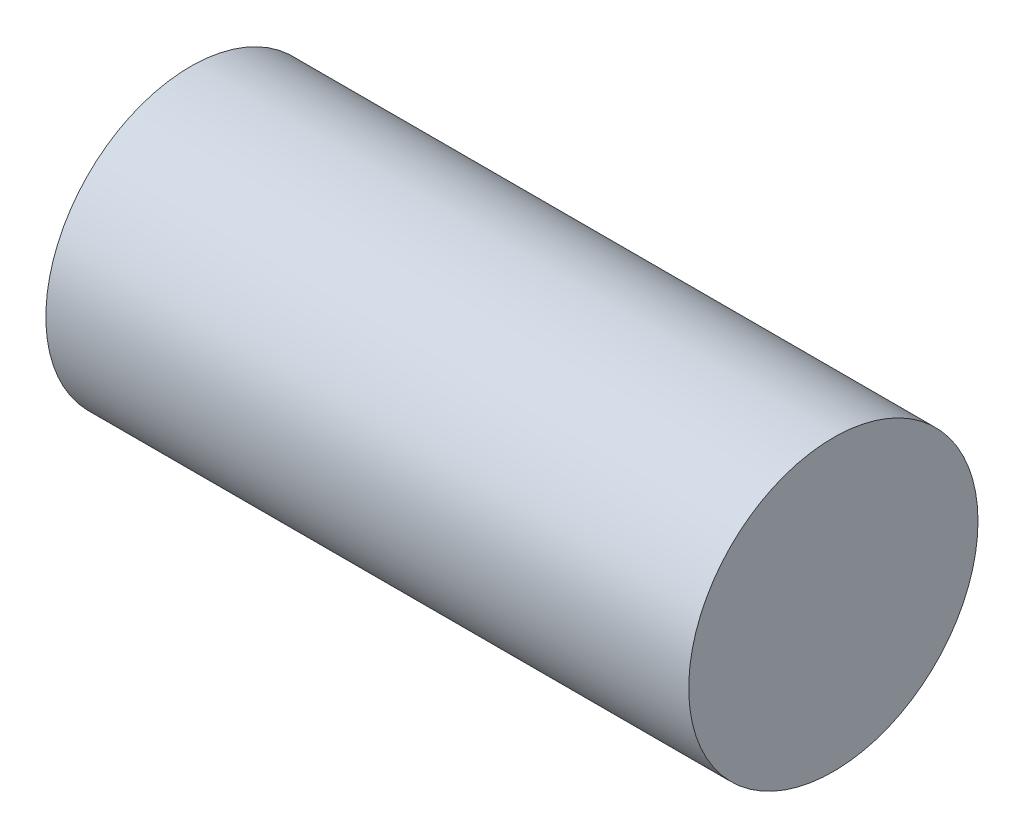
SolidWorks part; units mm, degrees
ref_plane "前视基准面" through (0, 0, 0) normal (0, 0, 1) x (1, 0, 0)
ref_plane "上视基准面" through (0, 0, 0) normal (0, 1, 0) x (1, 0, 0)
ref_plane "右视基准面" through (0, 0, 0) normal (1, 0, 0) x (0, 0, -1)
sketch "草图1" plane through (0, 0, 0) normal (1, 0, 0) x (0, 0, -1)
  circle A0 centre (-10.6399, -4.7061) radius 4.5
extrude "凸台-拉伸1" add sketch "草图1" along normal blind 20
